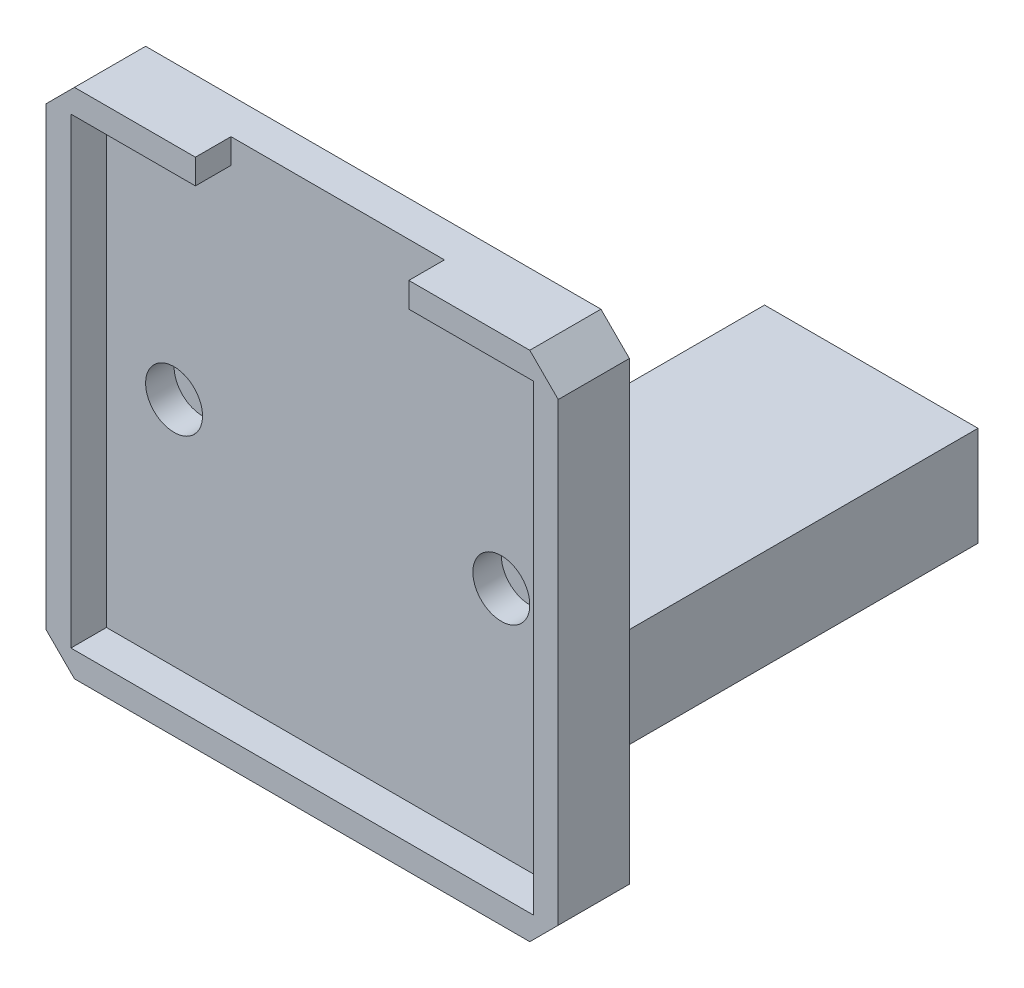
SolidWorks part; units mm, degrees
ref_plane "Front Plane" through (0, 0, 0) normal (0, 0, 1) x (1, 0, 0)
ref_plane "Top Plane" through (0, 0, 0) normal (0, 1, 0) x (1, 0, 0)
ref_plane "Right Plane" through (0, 0, 0) normal (1, 0, 0) x (0, 0, -1)
sketch "Sketch3" plane through (0, 0, 0) normal (0, 0, 1) x (1, 0, 0)
  line L1 (-18, 18) -> (18, 18)
  line L2 (-18, 18) -> (-18, -18)
  line L3 (-18, -18) -> (18, -18)
  line L4 (18, 18) -> (18, -18)
  line L5 (-18, 18) -> (18, -18) construction
  line L6 (-18, -18) -> (18, 18) construction
  point P0 (0, 0)
  dimension "D1" = 36
extrude "Boss-Extrude2" add sketch "Sketch3" along normal blind 5
sketch "Sketch4" plane through (0, 0, 5) normal (0, 0, 1) x (1, 0, 0)
  line L0 (18, 18) -> (-18, 18) construction
  line L1 (-16.25, 16.25) -> (16.25, 16.25)
  line L2 (-16.25, 16.25) -> (-16.25, -16.25)
  line L3 (-16.25, -16.25) -> (16.25, -16.25)
  line L4 (16.25, 16.25) -> (16.25, -16.25)
  line L5 (-16.25, 16.25) -> (16.25, -16.25) construction
  line L6 (-16.25, -16.25) -> (16.25, 16.25) construction
  line L7 (-7.5, 16.25) -> (7.5, 16.25)
  line L8 (-7.5, 16.25) -> (-7.5, 18)
  line L9 (-7.5, 18) -> (7.5, 18)
  line L10 (7.5, 16.25) -> (7.5, 18)
  point P0 (0, 0)
  point P13 (0, 18)
  line M6 (18, 18) -> (-18, 18)
  dimension "D1" = 32.5
  dimension "D2" = 15
extrude "Cut-Extrude1" cut sketch "Sketch4" against normal blind 2.5 contours L4 L1 L2 L3 | L1 L10 L8 M6
sketch "Sketch6" plane through (0, 0, 0) normal (1, 0, 0) x (0, 0, -1)
  line L0 (0, -11) -> (35, -11)
  line L1 (0, -11) -> (0, -18)
  line L2 (0, -18) -> (35, -18)
  line L3 (35, -18) -> (35, -11)
  dimension "D1" = 35
  dimension "D2" = 7
extrude "Boss-Extrude3" add sketch "Sketch6" along normal mid plane 15
chamfer "Chamfer1" distance 5 angle 45 2 edges at (-7.5, -14.5, 0) (7.5, -14.5, 0)
chamfer "Chamfer2" distance 2 angle 45 4 edges at (-18, 18, 2.5) (-18, -18, 2.5) (18, -18, 2.5) (18, 18, 2.5)
sketch "Sketch7" plane through (0, 0, 2.5) normal (0, 0, 1) x (1, 0, 0)
  line L0 (0, 0) -> (-18, 0) construction
  line L3 (0, 18) -> (0, -18) construction
  line L4 (7.5, 18) -> (-7.5, 18) construction
  line L5 (-18, 16) -> (-18, -16) construction
  circle A0 centre (-11.5, 0) radius 2
  circle A2 centre (11.5, 0) radius 2
  dimension "D1" = 4
  dimension "D2" = 6.5
extrude "Cut-Extrude2" cut sketch "Sketch7" against normal blind 2
chamfer "Chamfer3" distance 2 angle 45 1 edges at (0, -11, 0)
